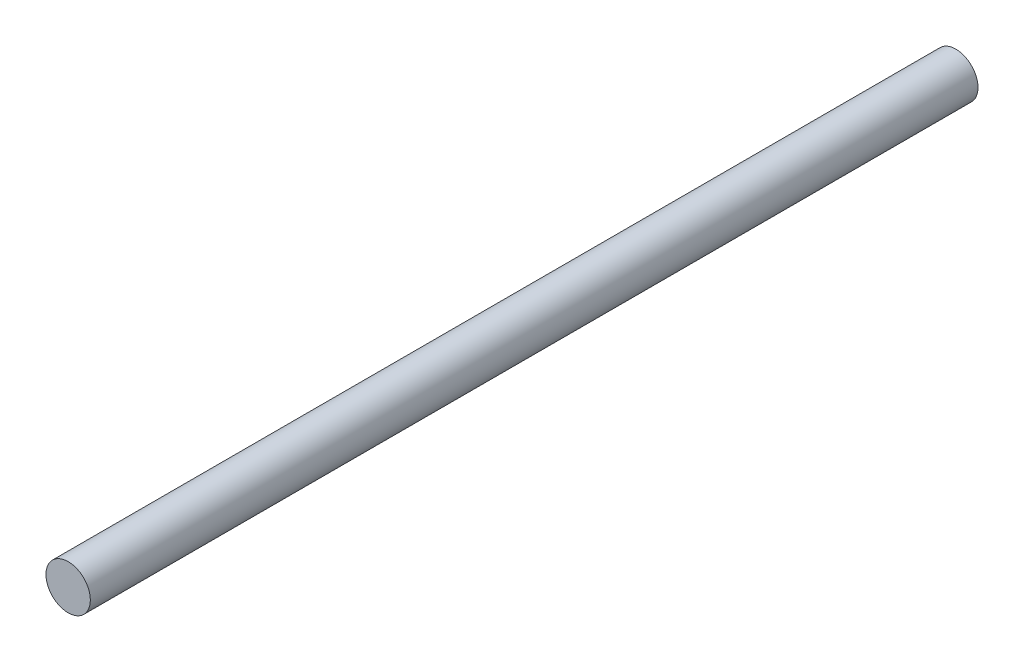
SolidWorks part; units mm, degrees
ref_plane "Front Plane" through (0, 0, 0) normal (0, 0, 1) x (1, 0, 0)
ref_plane "Top Plane" through (0, 0, 0) normal (0, 1, 0) x (1, 0, 0)
ref_plane "Right Plane" through (0, 0, 0) normal (1, 0, 0) x (0, 0, -1)
sketch "Sketch1" plane through (0, 0, 0) normal (0, 0, 1) x (1, 0, 0)
  circle A0 centre (0, 0) radius 2.5
  dimension "D1" = 5
extrude "Boss-Extrude1" add sketch "Sketch1" along normal blind 100
